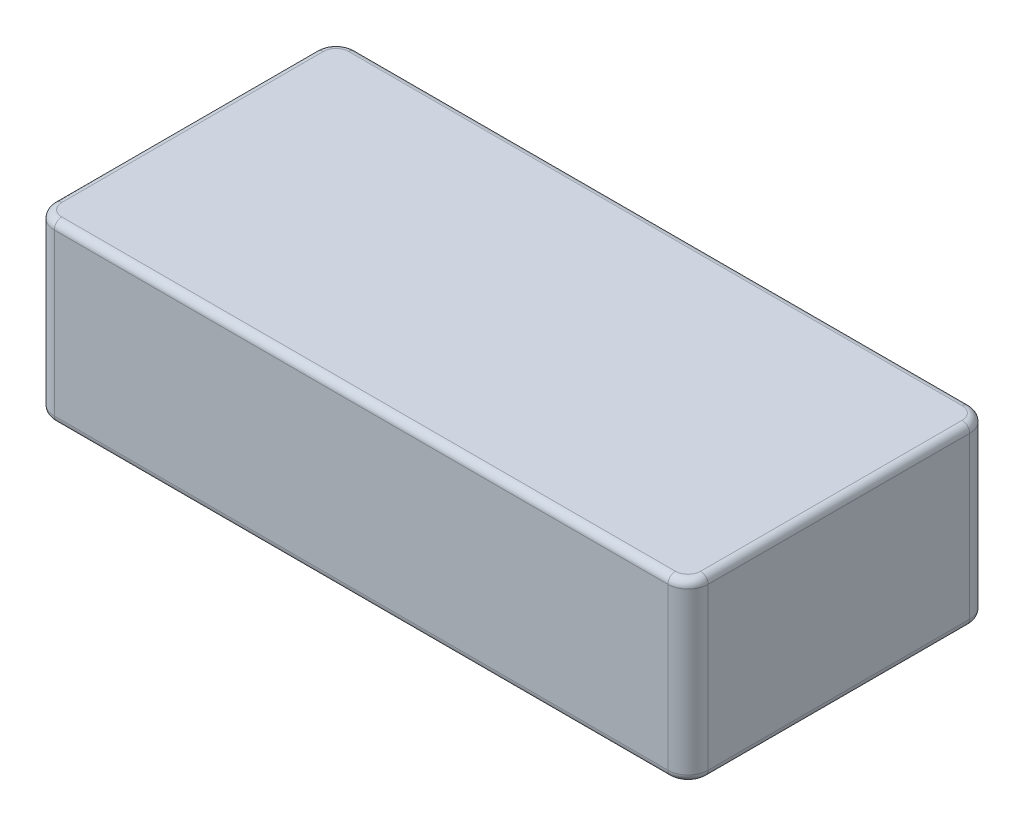
SolidWorks part; units mm, degrees
ref_plane "前视基准面" through (0, 0, 0) normal (0, 0, 1) x (1, 0, 0)
ref_plane "上视基准面" through (0, 0, 0) normal (0, 1, 0) x (1, 0, 0)
ref_plane "右视基准面" through (0, 0, 0) normal (1, 0, 0) x (0, 0, -1)
sketch "草图1" plane through (0, 0, 0) normal (0, 1, 0) x (1, 0, 0)
  line L1 (-130, 60) -> (130, 60)
  line L2 (-130, 60) -> (-130, -60)
  line L3 (-130, -60) -> (130, -60)
  line L4 (130, 60) -> (130, -60)
  point P4 (0, 60)
  point P6 (130, 0)
  dimension "D1" = 120
  dimension "D2" = 260
extrude "凸台-拉伸1" add sketch "草图1" along normal mid plane 70
fillet "圆角1" radius 8 4 edges at (130, 0, -60) (130, 0, 60) (-130, 0, 60) (-130, 0, -60)
fillet "圆角2" radius 3 16 edges at (-127.6569, -35, -57.6569) (-130, -35, 0) (-127.6569, -35, 57.6569) (0, -35, 60) (127.6569, -35, 57.6569) (130, -35, 0) (127.6569, -35, -57.6569) (0, -35, -60) (127.6569, 35, 57.6569) (0, 35, 60) (-127.6569, 35, 57.6569) (-130, 35, 0) (-127.6569, 35, -57.6569) (0, 35, -60) (127.6569, 35, -57.6569) (130, 35, 0)
sketch "草图2" plane through (-130, 0, 0) normal (-1, 0, 0) x (0, 0, 1)
  line L0 (0, 0) -> (-60, 0) construction
  line L1 (-60, -32) -> (-60, 32) construction
  circle A0 centre (-56.5, 4) radius 3.5
  circle A1 centre (-56.5, -4) radius 3.5
  point P4 (-56.2169, -1.8916)
  point P10 (0, 0)
  dimension "D1" = 7
  dimension "D2" = 8
extrude "凸台-拉伸2" add sketch "草图2" along normal mid plane 40
